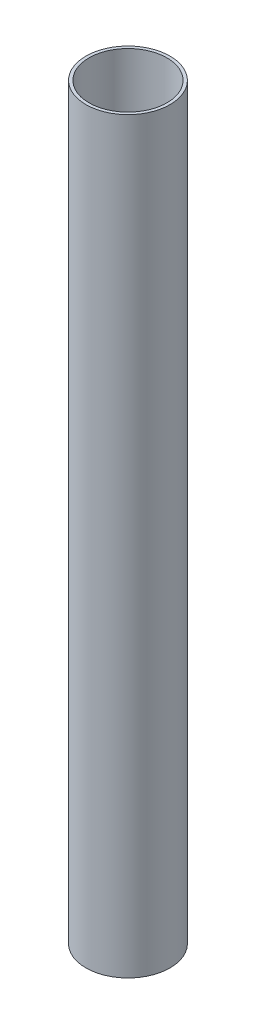
SolidWorks part; units mm, degrees
ref_plane "Front Plane" through (0, 0, 0) normal (0, 0, 1) x (1, 0, 0)
ref_plane "Top Plane" through (0, 0, 0) normal (0, 1, 0) x (1, 0, 0)
ref_plane "Right Plane" through (0, 0, 0) normal (1, 0, 0) x (0, 0, -1)
sketch "Sketch1" plane through (0, 0, 0) normal (0, 1, 0) x (1, 0, 0)
  circle A0 centre (0, 0) radius 25.5
  circle A1 centre (0, 0) radius 27.5
  dimension "D1" = 55
  dimension "D2" = 51
extrude "Boss-Extrude1" add sketch "Sketch1" along normal blind 489
